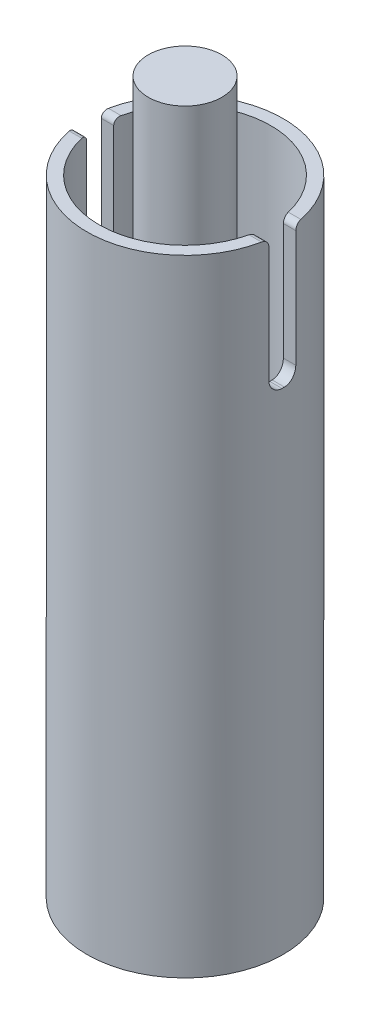
SolidWorks part; units mm, degrees
ref_plane "前视基准面" through (0, 0, 0) normal (0, 0, 1) x (1, 0, 0)
ref_plane "上视基准面" through (0, 0, 0) normal (0, 1, 0) x (1, 0, 0)
ref_plane "右视基准面" through (0, 0, 0) normal (1, 0, 0) x (0, 0, -1)
sketch "草图1" plane through (0, 0, 0) normal (0, 1, 0) x (1, 0, 0)
  circle A0 centre (0, 0) radius 8
  dimension "D1" = 16
extrude "凸台-拉伸1" add sketch "草图1" along normal blind 51
sketch "草图2" plane through (0, 51, 0) normal (0, 1, 0) x (1, 0, 0)
  circle A0 centre (0, 0) radius 7
  dimension "D1" = 14
extrude "切除-拉伸1" cut sketch "草图2" against normal blind 38
sketch "草图3" plane through (0, 0, 0) normal (1, 0, 0) x (0, 0, -1)
  line L0 (8, 51) -> (-8, 51) construction
  line L1 (-1.1, 62) -> (1.1, 62)
  line L2 (-1.1, 62) -> (-1.1, 40)
  line L3 (-1.1, 40) -> (1.1, 40)
  line L4 (1.1, 62) -> (1.1, 40)
  line L5 (-1.1, 62) -> (1.1, 40) construction
  line L6 (-1.1, 40) -> (1.1, 62) construction
  point P0 (0, 51)
  dimension "D1" = 22
  dimension "D2" = 2.2
extrude "切除-拉伸2" cut sketch "草图3" against normal through all both and the other way through all
fillet "圆角1" radius 0.5 4 edges at (7.4185, 51, 1.1) (-7.4185, 51, 1.1) (-7.4185, 51, -1.1) (7.4185, 51, -1.1)
fillet "圆角2" radius 1 4 edges at (7.4185, 40, 1.1) (-7.4185, 40, 1.1) (-7.4185, 40, -1.1) (7.4185, 40, -1.1)
sketch "草图4" plane through (0, 0, 0) normal (0, -1, 0) x (-1, 0, 0)
  circle A0 centre (0, 0) radius 3
  dimension "D1" = 6
sketch "草图5" plane through (0, 0, 0) normal (0, -1, 0) x (1, 0, 0)
  circle A0 centre (0, 5.5) radius 1.5
  arc A2 (6.8147, 1.6) -> (-6.8147, 1.6) centre (0, 0) ccw construction
  dimension "D1" = 3
extrude "切除-拉伸8" cut sketch "草图5" against normal blind 38
extrude "凸台-拉伸2" add sketch "草图4" against normal blind 58
